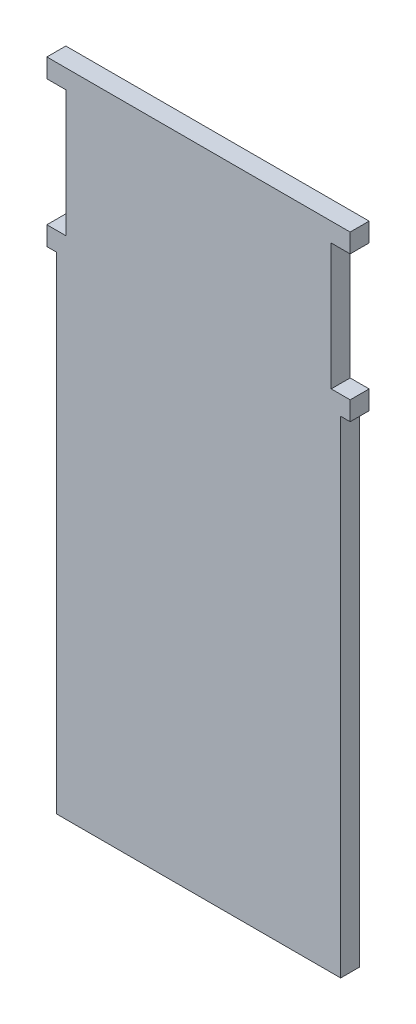
SolidWorks part; units mm, degrees
ref_plane "Plan de face" through (0, 0, 0) normal (0, 0, 1) x (1, 0, 0)
ref_plane "Plan de dessus" through (0, 0, 0) normal (0, 1, 0) x (1, 0, 0)
ref_plane "Plan de droite" through (0, 0, 0) normal (1, 0, 0) x (0, 0, -1)
sketch "Esquisse1" plane through (0, 0, 0) normal (0, 0, 1) x (1, 0, 0)
  line L1 (-1.5, -26) -> (0, -26)
  line L2 (-46.5, -26) -> (-46.5, -103)
  line L3 (-46.5, -103) -> (-1.5, -103)
  line L4 (-1.5, -26) -> (-1.5, -103)
  line L6 (0, -26) -> (0, -23)
  line L7 (0, -23) -> (-3, -23)
  line L8 (-3, -23) -> (-3, -3)
  line L9 (-3, -3) -> (0, -3)
  line L10 (0, -3) -> (0, 0)
  line L11 (0, 0) -> (-48, 0)
  line L12 (-24, -13) -> (-24, 13.3651) construction
  line L13 (-48, -3) -> (-48, 0)
  line L14 (-45, -3) -> (-48, -3)
  line L15 (-45, -23) -> (-45, -3)
  line L16 (-48, -23) -> (-45, -23)
  line L17 (-48, -26) -> (-48, -23)
  line L18 (-46.5, -26) -> (-48, -26)
  point P0 (0, 0)
  dimension "D4" = 45
  dimension "D7" = 3
  dimension "D19" = 3
  dimension "D20" = 3
  dimension "D21" = 1.5
  dimension "D22" = 3
  dimension "D23" = 20
  dimension "D24" = 103
extrude "Extrusion1" add sketch "Esquisse1" along normal blind 3
